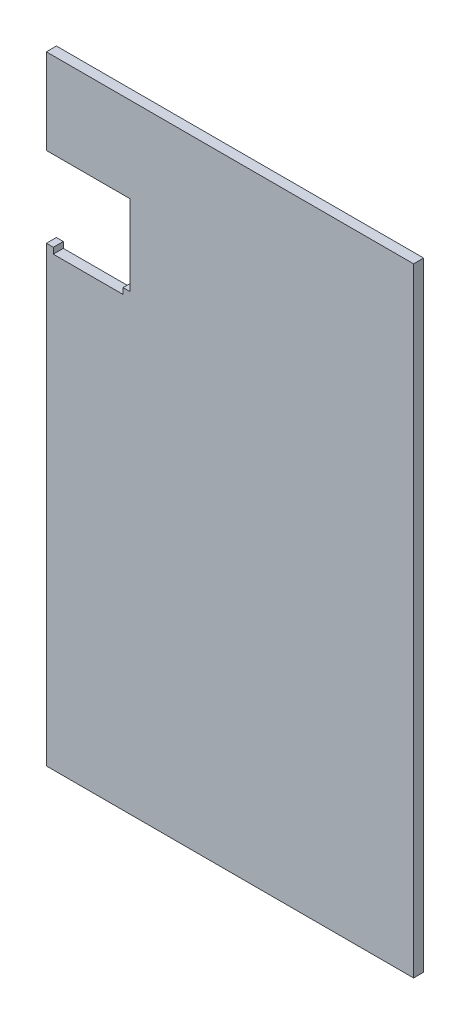
SolidWorks part; units mm, degrees
ref_plane "Front Plane" through (0, 0, 0) normal (0, 0, 1) x (1, 0, 0)
ref_plane "Top Plane" through (0, 0, 0) normal (0, 1, 0) x (1, 0, 0)
ref_plane "Right Plane" through (0, 0, 0) normal (1, 0, 0) x (0, 0, -1)
sketch "Sketch1" plane through (0, 0, 0) normal (0, 0, 1) x (1, 0, 0)
  line L1 (-32.236, 22.6895) -> (77.3897, 22.6895)
  line L2 (-32.236, 22.6895) -> (-32.236, -161.9293)
  line L3 (-32.236, -161.9293) -> (77.3897, -161.9293)
  line L4 (77.3897, 22.6895) -> (77.3897, -161.9293)
  dimension "D1" = 184.6189
  dimension "D2" = 109.6257
extrude "Boss-Extrude2" add sketch "Sketch1" along normal blind 3
sketch "Sketch2" plane through (0, 0, 3) normal (0, 0, 1) x (1, 0, 0)
  line L0 (-32.236, 22.6895) -> (-32.236, -161.9293) construction
  line L1 (-7.236, -2.8105) -> (-32.236, -2.8105)
  line L2 (-7.236, -2.8105) -> (-7.236, -26.8105)
  line L3 (-7.236, -26.8105) -> (-32.236, -26.8105)
  line L4 (-32.236, -2.8105) -> (-32.236, -26.8105)
  line L5 (-32.236, -26.8105) -> (-7.236, -26.8105) construction
extrude "Cut-Extrude1" cut sketch "Sketch2" against normal blind 10
sketch "Sketch3" plane through (0, 0, 0) normal (0, 0, -1) x (-1, 0, 0)
  line L0 (32.236, -26.8105) -> (7.236, -26.8105) construction
  line L1 (9.3431, -26.8105) -> (30.1686, -26.8105)
  line L2 (9.3431, -26.8105) -> (9.3431, -28.5872)
  line L3 (9.3431, -28.5872) -> (30.1686, -28.5872)
  line L4 (30.1686, -26.8105) -> (30.1686, -28.5872)
extrude "Cut-Extrude2" cut sketch "Sketch3" against normal blind 10
